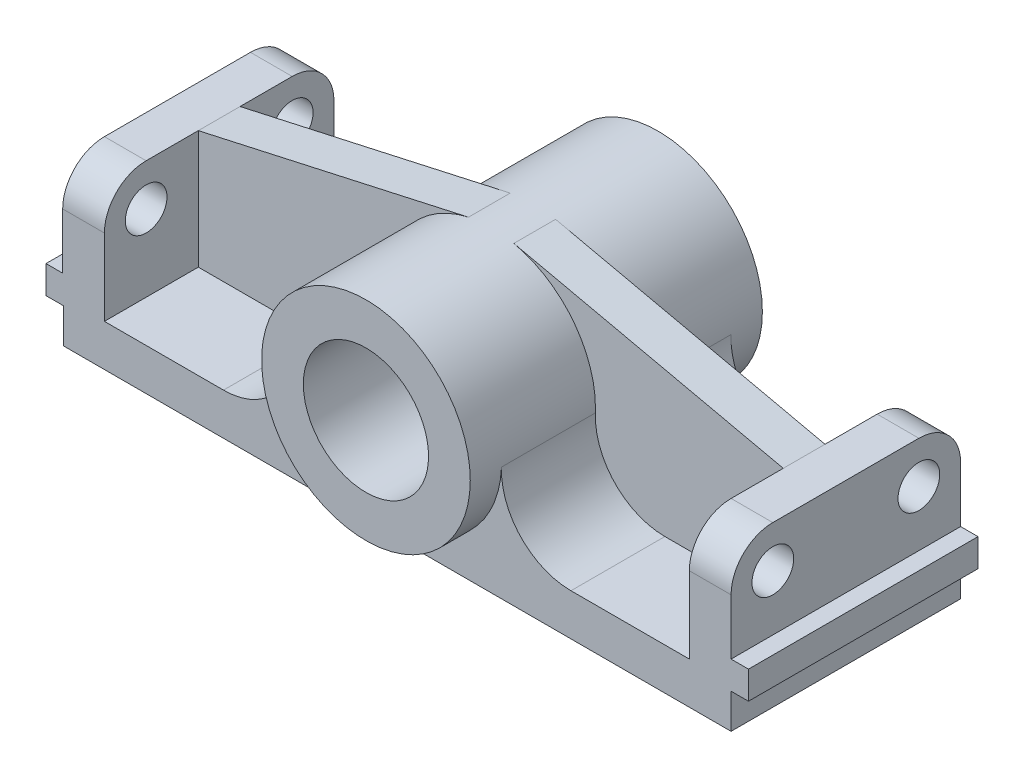
SolidWorks part; units mm, degrees
ref_plane "Front Plane" through (0, 0, 0) normal (0, 0, 1) x (1, 0, 0)
ref_plane "Top Plane" through (0, 0, 0) normal (0, 1, 0) x (1, 0, 0)
ref_plane "Right Plane" through (0, 0, 0) normal (1, 0, 0) x (0, 0, -1)
sketch "Sketch1" plane through (0, 0, 0) normal (0, 0, 1) x (1, 0, 0)
  circle A0 centre (0, 0) radius 18
  circle A1 centre (0, 0) radius 30
  dimension "D1" = 36
  dimension "D2" = 60
extrude "Boss-Extrude1" add sketch "Sketch1" along normal blind 84
ref_plane "Plane1" through (0, 0, 9) normal (0, 0, 1) x (1, 0, 0)
sketch "Sketch2" plane through (0, 0, 9) normal (0, 0, 1) x (1, 0, 0)
  line L0 (96, -24) -> (101, -24)
  line L1 (101, -24) -> (101, -16)
  line L2 (101, -16) -> (96, -16)
  line L3 (96, -16) -> (96, 12)
  line L4 (96, 12) -> (84, 12)
  line L5 (84, 12) -> (84, -22)
  line L6 (84, -22) -> (49.96, -22)
  line L7 (96, -24) -> (96, -34)
  line L8 (96, -34) -> (-96, -34)
  line L9 (-96, -34) -> (-96, -24)
  line L10 (-96, -24) -> (-101, -24)
  line L11 (-101, -24) -> (-101, -16)
  line L12 (-101, -16) -> (-96.2042, -16)
  line L13 (-96.2042, -16) -> (-96.2042, 12)
  line L14 (-96.2042, 12) -> (-84.2042, 12)
  line L15 (-84.2042, 12) -> (-84.2042, -22)
  line L16 (-84.2042, -22) -> (-49.96, -22)
  line L17 (0, 0) -> (0, -34) construction
  line L18 (-30, 0) -> (30, 0) construction
  arc A0 (-49.96, -22) -> (-29.976, -1.2) centre (-49.96, -2) ccw
  circle A1 centre (0, 0) radius 30 construction
  arc A2 (49.96, -22) -> (29.976, -1.2) centre (49.96, -2) cw
  circle A4 centre (0, 0) radius 30
  arc A5 (-29.976, -1.2) -> (29.976, -1.2) centre (0, 0) ccw
  dimension "D10" = 34
  dimension "D18" = 20
  dimension "D19" = 20
  dimension "D2" = 96
  dimension "D3" = 192
  dimension "D4" = 10
  dimension "D5" = 8
  dimension "D6" = 46
  dimension "D7" = 12
  dimension "D8" = 101
  dimension "D9" = 12
  dimension "D11" = 101
  dimension "D12" = 12
  dimension "D13" = 8
  dimension "D14" = 10
  dimension "D15" = 12
  dimension "D16" = 46
  dimension "D17" = 4.7958
  dimension "D20" = 0
extrude "Boss-Extrude3" add sketch "Sketch2" along normal blind 66
sketch "Sketch3" plane through (96, 0, 0) normal (1, 0, 0) x (0, 0, -1)
  line L0 (-75, 0) -> (-9, 0) construction
  line L1 (-75, -16) -> (-75, 12) construction
  line L2 (-9, 35.2) -> (-9, -35.2) construction
  line L3 (-42, 12) -> (-42, -34) construction
  line L4 (-75, 12) -> (-9, 12) construction
  line L5 (-75, -34) -> (-9, -34) construction
  circle A0 centre (-63, 0) radius 6
  circle A1 centre (-21, 0) radius 6
  dimension "D2" = 12
  dimension "D3" = 12
  dimension "D1" = 34
  dimension "D4" = 21
  dimension "D5" = 21
extrude "Cut-Extrude1" cut sketch "Sketch3" against normal up to next and the other way through all
fillet "Fillet1" radius 12 2 edges at (90, 12, 9) (90, 12, 75)
sketch "Sketch4" plane through (-96.2042, 0, 0) normal (-1, 0, 0) x (0, 0, 1)
  line L0 (75, 0) -> (9, 0) construction
  line L2 (75, 12) -> (75, -16) construction
  line L3 (9, -35.2) -> (9, 35.2) construction
  line L4 (42, 12) -> (42, -16) construction
  line L5 (75, 12) -> (9, 12) construction
  line L6 (75, -16) -> (9, -16) construction
  circle A0 centre (21, 0) radius 6
  circle A1 centre (63, 0) radius 6
  dimension "D2" = 12
  dimension "D3" = 12
  dimension "D1" = 34
  dimension "D4" = 21
  dimension "D5" = 21
extrude "Cut-Extrude2" cut sketch "Sketch4" against normal up to next
fillet "Fillet2" radius 12 2 edges at (-90.2042, 12, 9) (-90.2042, 12, 75)
ref_plane "Plane2" through (0, 0, 42) normal (0, 0, 1) x (1, 0, 0)
sketch "Sketch5" plane through (0, 0, 42) normal (0, 0, 1) x (1, 0, 0)
  line L1 (-84.2042, 12) -> (-6.515, 29.284)
  circle A0 centre (0, 0) radius 30 construction
rib "Rib1" sketch "Sketch5" sketch "Sketch5" thickness 12 extrusion direction parallel to sketch draft on no parameters "D1"=12
sketch "Sketch6" plane through (0, 0, 42) normal (0, 0, 1) x (1, 0, 0)
  line L0 (84, 12) -> (6.5314, 29.2804)
  circle A0 centre (0, 0) radius 30 construction
rib "Rib2" sketch "Sketch6" sketch "Sketch6" thickness 12 extrusion direction parallel to sketch draft on no parameters "D1"=12
